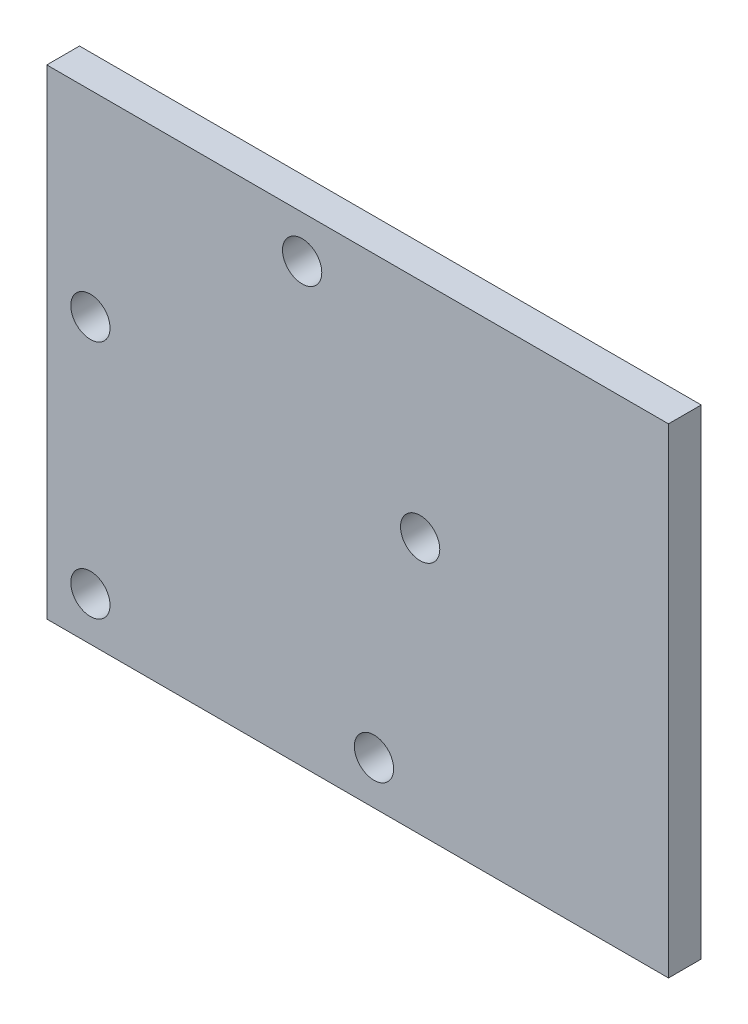
SolidWorks part; units mm, degrees
ref_plane "Front Plane" through (0, 0, 0) normal (0, 0, 1) x (1, 0, 0)
ref_plane "Top Plane" through (0, 0, 0) normal (0, 1, 0) x (1, 0, 0)
ref_plane "Right Plane" through (0, 0, 0) normal (1, 0, 0) x (0, 0, -1)
sketch "Sketch1" plane through (0, 0, 0) normal (0, 0, 1) x (1, 0, 0)
  line L0 (4, 0) -> (4, 44) construction
  line L1 (0, 0) -> (57, 0)
  line L2 (0, 0) -> (0, 44)
  line L3 (0, 44) -> (57, 44)
  line L4 (57, 0) -> (57, 44)
  line L5 (0, 4) -> (57, 4) construction
  circle A0 centre (4, 4) radius 1.8
  circle A1 centre (30, 4) radius 1.8
  circle A2 centre (4, 26) radius 1.8
  circle A3 centre (23.4115, 40.1136) radius 1.8
  circle A5 centre (34.2308, 23.5474) radius 1.8
  dimension "D3" = 3.6
  dimension "D4" = 22
  dimension "D1" = 57
  dimension "D2" = 44
  dimension "D5" = 4
  dimension "D6" = 4
  dimension "D7" = 26
  dimension "D8" = 24
  dimension "D9" = 36
  dimension "D10" = 41
  dimension "D11" = 20
extrude "Boss-Extrude1" add sketch "Sketch1" along normal blind 3
